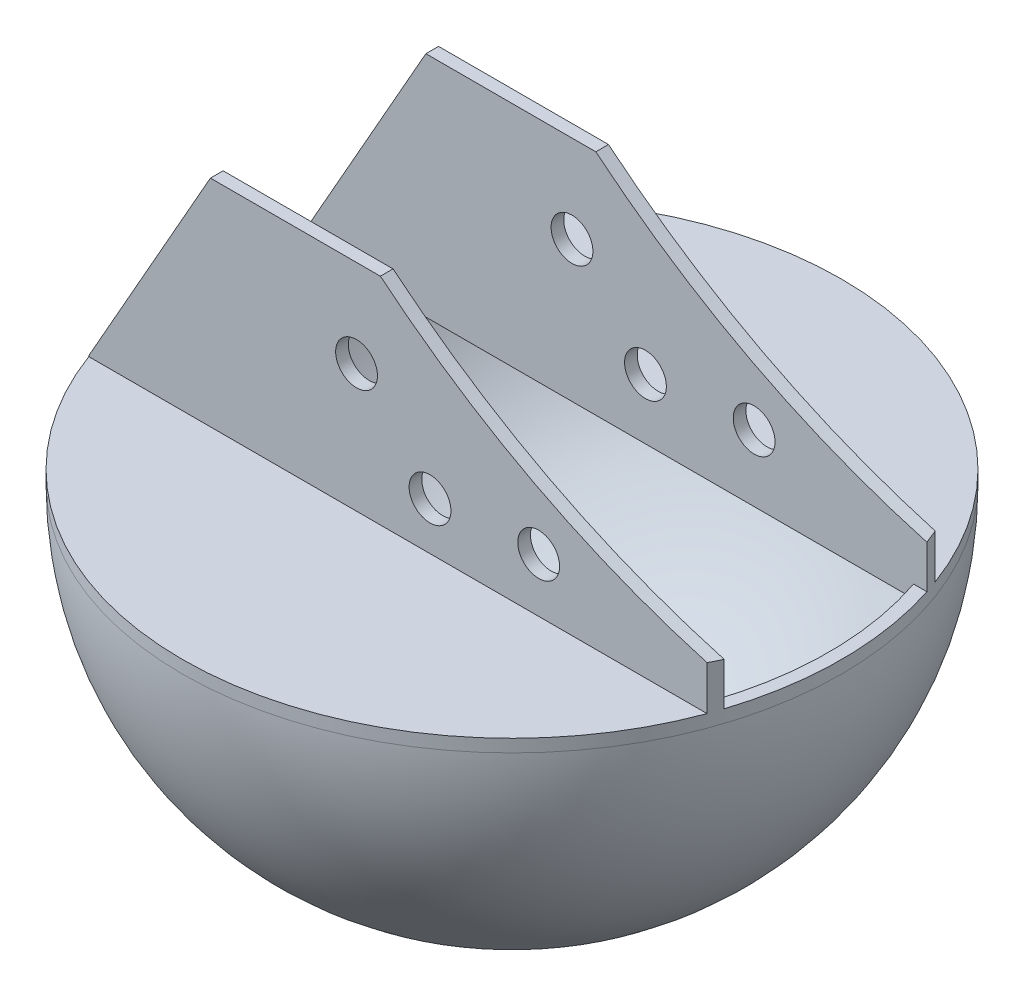
SolidWorks part; units mm, degrees
ref_plane "前视基准面" through (0, 0, 0) normal (0, 0, 1) x (1, 0, 0)
ref_plane "上视基准面" through (0, 0, 0) normal (0, 1, 0) x (1, 0, 0)
ref_plane "右视基准面" through (0, 0, 0) normal (1, 0, 0) x (0, 0, -1)
sketch "草图1" plane through (0, 0, 0) normal (0, 0, 1) x (1, 0, 0)
  line L0 (0, 45.1736) -> (0, -47.6456) construction
  line L1 (0, -26) -> (0, 26)
  arc A0 (0, 26) -> (0, -26) centre (0, 0) ccw
  dimension "D1" = 52
revolve "旋转1" add sketch "草图1" angle 360 about L0
sketch "草图2" plane through (0, 0, 0) normal (0, 1, 0) x (1, 0, 0)
  circle A0 centre (0, 0) radius 26 construction
  circle A1 centre (0, 0) radius 26
extrude "切除-拉伸1" cut sketch "草图2" along normal blind 94
sketch "草图3" plane through (0, 0, 0) normal (0, 1, 0) x (1, 0, 0)
  line L0 (0, 28.6811) -> (0, -28.9502) construction
  line L1 (0, -25) -> (0, 25)
  arc A0 (0, 25) -> (0, -25) centre (0, 0) ccw
  dimension "D1" = 50
revolve "切除-旋转3" cut sketch "草图3" angle 360 about L0
sketch "草图5" plane through (0, 0, 0) normal (0, 1, 0) x (1, 0, 0)
  circle A0 centre (0, 0) radius 26 construction
  circle A1 centre (0, 0) radius 25 construction
  circle A2 centre (0, 0) radius 26
  circle A3 centre (0, 0) radius 25
extrude "凸台-拉伸1" add sketch "草图5" along normal blind 1
sketch "草图6" plane through (0, 1, 0) normal (0, 1, 0) x (1, 0, 0)
  line L0 (-23.6854, 8) -> (23.6854, 8)
  line L1 (-31.9922, 0) -> (34.2461, 0) construction
  line L2 (-23.6854, -8) -> (23.6854, -8)
  circle A0 centre (0, 0) radius 25 construction
  circle A1 centre (0, 0) radius 25 construction
  arc A2 (-23.6854, -8) -> (23.6854, -8) centre (0, 0) ccw
  arc A3 (23.6854, 8) -> (-23.6854, 8) centre (0, 0) ccw
  dimension "D1" = 16
extrude "凸台-拉伸2" add sketch "草图6" against normal blind 1
sketch "草图7" plane through (0, 1, 0) normal (0, 1, 0) x (1, 0, 0)
  line L0 (-24.3926, 9) -> (24.3926, 9)
  line L1 (23.6854, 8) -> (24.7386, 8)
  line L2 (23.6854, 8) -> (-24.7386, 8)
  line L3 (-29.0795, 0) -> (28.2209, 0) construction
  line L4 (23.6854, -8) -> (-24.7386, -8)
  line L5 (23.6854, -8) -> (24.7386, -8)
  line L6 (-24.3926, -9) -> (24.3926, -9)
  circle A0 centre (0, 0) radius 26 construction
  arc A1 (-24.3926, 9) -> (-24.7386, 8) centre (0, 0) ccw
  arc A2 (24.7386, 8) -> (24.3926, 9) centre (0, 0) ccw
  arc A3 (24.7386, -8) -> (24.3926, -9) centre (0, 0) cw
  arc A4 (-24.3926, -9) -> (-24.7386, -8) centre (0, 0) cw
  dimension "D1" = 1
extrude "凸台-拉伸3" add sketch "草图7" along normal blind 17
sketch "草图8" plane through (0, 0, 9) normal (0, 0, 1) x (1, 0, 0)
  line L0 (-14.7959, 18) -> (-24.4331, 1)
  line L1 (-24.3926, 18) -> (24.3926, 18) construction
  line L2 (-24.4331, 1) -> (-27.8656, 20.822)
  line L3 (-27.8656, 20.822) -> (-14.7959, 18)
  line L4 (0.6877, 18) -> (34.87, 20.822)
  line L5 (34.87, 20.822) -> (23.0837, 6.6669)
  arc A1 (0.6877, 18) -> (23.0837, 6.6669) centre (30.1711, 48.4681) ccw
extrude "切除-拉伸2" cut sketch "草图8" against normal blind 36
sketch "草图9" plane through (0, 0, 9) normal (0, 0, 1) x (1, 0, 0)
  line L0 (23.0837, 6.6669) -> (25.7021, 6.22)
  line L1 (25.7021, 6.22) -> (22.5831, 9.596)
  line L2 (22.5831, 9.596) -> (23.0837, 6.6669)
  arc A0 (0.6877, 18) -> (23.0837, 6.6669) centre (30.1711, 48.4681) ccw construction
extrude "切除-拉伸3" cut sketch "草图9" against normal blind 36
sketch "草图11" plane through (0, 0, 9) normal (0, 0, 1) x (1, 0, 0)
  circle A3 centre (11.1048, 5.2409) radius 1.65
  circle A4 centre (2.53, 4.7448) radius 1.65
  circle A5 centre (-3.2666, 11.0829) radius 1.65
extrude "切除-拉伸4" cut sketch "草图11" against normal blind 36
sketch "草图12" plane through (0, 0, 9) normal (0, 0, 1) x (1, 0, 0)
  line L0 (-24.3926, 1.0714) -> (-24.3926, 1)
  line L1 (-24.3926, 1) -> (-24.8395, 1)
  line L2 (-24.7386, 1) -> (-26, 1) construction
  line L3 (-24.8395, 1) -> (-24.8395, 4.0368)
  line L4 (-24.8395, 4.0368) -> (-24.3926, 1.0714)
  line L5 (23.434, 8.3508) -> (25.2949, 6.4899)
  line L6 (25.2949, 6.4899) -> (25.2949, 10.2116)
  line L7 (25.2949, 10.2116) -> (23.434, 8.3508)
extrude "切除-拉伸5" cut sketch "草图12" against normal blind 24
sketch "草图13" plane through (0, 0, 9) normal (0, 0, 1) x (1, 0, 0)
  line L0 (-14.7959, 18) -> (0.6877, 18) construction
  line L1 (24.7386, 6.3844) -> (24.7386, 1) construction
  line L2 (-1.3852, 18) -> (8.4168, 26.7221)
  line L3 (8.4168, 26.7221) -> (30.3245, 6.5171)
  line L4 (30.3245, 6.5171) -> (24.7386, 4.3832)
  arc A0 (-1.3852, 18) -> (24.7386, 4.3832) centre (43.7023, 72.6324) ccw
extrude "切除-拉伸6" cut sketch "草图13" against normal blind 21
